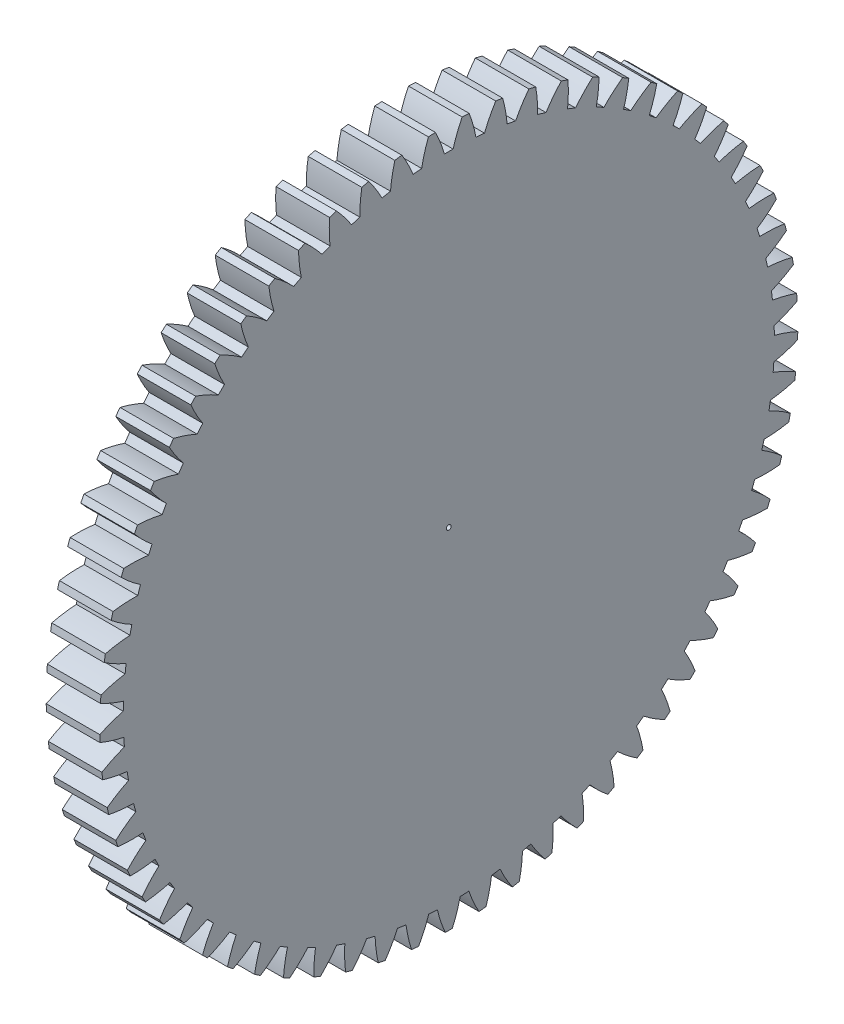
SolidWorks part; units mm, degrees
ref_plane "Plane1" through (0, 0, 0) normal (0, 0, 1) x (1, 0, 0)
ref_plane "Plane2" through (0, 0, 0) normal (0, 1, 0) x (1, 0, 0)
ref_plane "Plane3" through (0, 0, 0) normal (1, 0, 0) x (0, 0, -1)
other "Configuration Table"
sketch "HoldingSke" plane through (0, 0, 0) normal (0, 1, 0) x (1, 0, 0)
  line L0 (0, 0) -> (0.2415, -0.5179)
  line L1 (-15, 0) -> (100, 0) construction
  line L2 (0, 0) -> (-2.1039, 2.3779)
  line L3 (0, 0) -> (-11.863, 4.5341)
  line L4 (0, 0) -> (3.6497, 7.8269)
  line L5 (0, 0) -> (-46.8476, -17.4728)
  line L6 (0, 0) -> (-7.4607, -5.0337)
  line L7 (-2.1039, 2.3779) -> (8.6586, 51.2059)
  line L8 (-76.2, 54.61) -> (-76.1, 54.61)
  line L9 (-71.009, 38.7566) -> (-53.1078, 45.2721)
  line L10 (-76.2, 71.12) -> (104.1128, 71.12)
  line L11 (0, 0) -> (-9, 0)
  line L12 (-76.2, 101.6) -> (-76.147, 101.6)
  line L13 (24.9733, 27.94) -> (52.9518, 28.4284)
  line L14 (24.9733, 27.94) -> (24.9743, 27.94)
  line L15 (24.9733, 27.94) -> (100.4006, 29.5858)
  line L16 (-63.627, -1.75) -> (-12.827, -1.75)
  circle A0 centre (0, 0) radius 0.4
  circle A1 centre (0, 0) radius 37.5
  circle A2 centre (0, 0) radius 37.5
  circle A3 centre (0, 0) radius 0.4
  dimension "MHD" = 75
  dimension "Hub_dia" = 75
  dimension "Bore" = 0.8
  dimension "MBD" = 0.8
  dimension "Num_teeth" = 65
  dimension "Pitch" = 0.5714
  dimension "Overall_len" = 50
  dimension "Show_teeth" = 65
  dimension "Thickness" = 9
  dimension "OAL" = 50.0001
  dimension "T_dim" = 0.1
  dimension "Ap" = 20
  dimension "H" = 19.05
  dimension "Pitch_radius" = 180.3128
  dimension "Width" = 9
  dimension "Backlash" = 0.053
  dimension "Addendum_fac" = 1
  dimension "Dedendum_fac" = 1.25
  dimension "Clearance_fac" = 0.25
  dimension "Dedendum_add" = 0.001
  dimension "Module" = 1.75
sketch "BasProSke" plane through (0, 0, 0) normal (0, 1, 0) x (1, 0, 0)
  line L0 (-10, 0) -> (60, 0) construction
  line L1 (0, 0) -> (0, 58.625)
  line L2 (0, 0) -> (9, 0)
  line L3 (9, 0) -> (9, 58.625)
  line L4 (9, 58.625) -> (0, 58.625)
  dimension "Thickness" = 9
  dimension "Diameter" = 117.25
revolve "Base-Revolve" add sketch "BasProSke" angle 360 about L0
sketch "TooCutSke" plane through (0, 0, 0) normal (1, 0, 0) x (0, 0, -1)
  line L1 (0, 0) -> (0, 107) construction
  line L2 (0, 0) -> (-1.4671, 56.8561) construction
  line L3 (0, 0) -> (-5.4943, 113.5883) construction
  line L4 (-1.4671, 56.8561) -> (-2.7471, 56.7942) construction
  arc A0 (0.7251, 54.6817) -> (-0.7251, 54.6817) centre (0, 0) ccw
  arc A1 (2.2522, 58.6071) -> (-2.2522, 58.6071) centre (0, 0) ccw
  circle A2 centre (0, 0) radius 56.875 construction
  circle A3 centre (0, 0) radius 53.445 construction
  arc A4 (-0.7251, 54.6817) -> (-2.2522, 58.6071) centre (-22.5998, 48.4316) ccw
  arc A5 (2.2522, 58.6071) -> (0.7251, 54.6817) centre (22.5998, 48.4316) ccw
  dimension "Root_dia" = 109.373
  dimension "Overcut_dia" = 117.3008
  dimension "Pitch_dia" = 113.75
  dimension "Base_dia" = 106.89
  dimension "Flank_rad" = 22.75
  dimension "Half_ang" = 2.769
  dimension "Half_CT" = 1.2816
extrude "ToothCut" cut sketch "TooCutSke" along normal through all
fillet "Breaks" [suppressed] radius 0.035
fillet "RootFillets" [suppressed] radius 0.4385
pattern_circular "TeethCuts" count 65 every 5.538 about axis through (-10, 0, 0) along (1, 0, 0) of "ToothCut", "RootFillets", "Breaks"
sketch "HubNeaOneSke" plane through (0, 0, 0) normal (-1, 0, 0) x (0, 0, 1)
  circle A0 centre (0, 0) radius 37.5
  dimension "Diameter" = 75
extrude "HubNearOne" [suppressed] add sketch "HubNeaOneSke" along normal blind 41.0001
sketch "HubNeaBotSke" plane through (0, 0, 0) normal (-1, 0, 0) x (0, 0, 1)
  circle A0 centre (0, 0) radius 37.5
  dimension "Diameter" = 75
extrude "HubNearBoth" [suppressed] add sketch "HubNeaBotSke" along normal blind 20.5
ref_plane "FarPln" through (9, 0, 0) normal (1, 0, 0) x (0, 0, -1)
sketch "HubFarSke" plane through (9, 0, 0) normal (1, 0, 0) x (0, 0, -1)
  circle A0 centre (0, 0) radius 37.5
  dimension "Diameter" = 75
extrude "HubFar" [suppressed] add sketch "HubFarSke" along normal blind 20.5
sketch "BorSke" plane through (0, 0, 0) normal (1, 0, 0) x (0, 0, -1)
  circle A0 centre (0, 0) radius 0.4
  dimension "Diameter" = 0.8
extrude "Bore" cut sketch "BorSke" along normal mid plane 100.0001
sketch "KeySke" plane through (0, 0, 0) normal (1, 0, 0) x (0, 0, -1)
  line L0 (-0.05, 0) -> (-0.05, 0.5)
  line L1 (-0.05, 0.5) -> (0.05, 0.5)
  line L2 (0.05, 0.5) -> (0.05, 0)
  line L3 (0, 0) -> (0, 34) construction
  line L4 (-0.05, 0) -> (0.05, 0)
  dimension "Offset" = 0.5
  dimension "Width" = 0.1
extrude "Keyway" [suppressed] cut sketch "KeySke" along normal mid plane 100.0001
pattern_circular "Keyway2" [suppressed] count 2 every 90 about axis through (-10, 0, 0) along (1, 0, 0)
equation "' \"Module@HoldingSke\" = 6.35"
equation "' \"Num_teeth@HoldingSke\" = 12"
equation "' \"Ap@HoldingSke\" =  20"
equation "' \"Ap@HoldingSke\" = 20"
equation "' \"Width@HoldingSke\" = 0.5 * 25.4"
equation "' \"Hub_dia@HoldingSke\"= 1 * 25.4"
equation "' \"Hub_dia@HoldingSke\" = 1 * 25.4"
equation "' \"Overall_len@HoldingSke\" = 1.0 * 25.4"
equation "' \"Bore@HoldingSke\" = 0.75 * 25.4"
equation "' \"T_dim@HoldingSke\" = 0.1 * 25.4"
equation "' \"Width@KeySke\" = 0.25 * 25.4"
equation "' \"Show_teeth@HoldingSke\" = 13"
equation "' \"Backlash@HoldingSke\" = 0.009 * 25.4"
equation "' \"Addendum_fac@HoldingSke\" = 1.0"
equation "' \"Dedendum_fac@HoldingSke\" = 1.25"
equation "' \"Dedendum_add@HoldingSke\" = 0.00005 * 25.4"
equation "' \"Clearance_fac@HoldingSke\" = 0.25"
equation "\"Pitch@HoldingSke\" = 1 / \"Module@HoldingSke\""
equation "\"Overcut_dia@TooCutSke\" = (\"Num_teeth@HoldingSke\" + 2 * \"Addendum_fac@HoldingSke\") / \"Pitch@HoldingSke\" + 0.002 * 25.4"
equation "\"Pitch_dia@TooCutSke\" = \"Num_teeth@HoldingSke\" / \"Pitch@HoldingSke\""
equation "\"Base_dia@TooCutSke\" = \"Num_teeth@HoldingSke\" / \"Pitch@HoldingSke\" * cos((\"Ap@HoldingSke\"  * 3.14159265 / 180))"
equation "\"Root_dia@TooCutSke\" = (\"Num_teeth@HoldingSke\" + 2) / \"Pitch@HoldingSke\" - 2 * (\"Addendum_fac@HoldingSke\" + \"Dedendum_fac@HoldingSke\") / \"Pitch@HoldingSke\" - \"Dedendum_add@HoldingSke\" * 2"
equation "\"Half_ang@TooCutSke\" = 180 / \"Num_teeth@HoldingSke\""
equation "\"Half_CT@TooCutSke\" = \"Num_teeth@HoldingSke\" / \"Pitch@HoldingSke\" * sin((3.14159265 / 2 / \"Num_teeth@HoldingSke\")) / 2 - 7 * \"Backlash@HoldingSke\" / 4"
equation "\"Flank_rad@TooCutSke\" = \"Num_teeth@HoldingSke\" / \"Pitch@HoldingSke\" / 5"
equation "\"Radius@RootFillets\" = \"Clearance_fac@HoldingSke\" / \"Pitch@HoldingSke\" + \"Dedendum_add@HoldingSke\""
equation "\"Break_rad@Breaks\" = 0.02 / \"Pitch@HoldingSke\""
equation "\"Thickness@HoldingSke\" = \"Width@HoldingSke\""
equation "\"OAL@HoldingSke\" = \"Thickness@HoldingSke\""
equation "\"MHD@HoldingSke\" = (\"Num_teeth@HoldingSke\" + 2) / \"Pitch@HoldingSke\" - 2 * (\"Addendum_fac@HoldingSke\" + \"Dedendum_fac@HoldingSke\")  / \"Pitch@HoldingSke\" - \"Dedendum_add@HoldingSke\" * 2"
equation "\"MBD@HoldingSke\" = (\"Num_teeth@HoldingSke\" + 2) / \"Pitch@HoldingSke\" - 2 * (\"Addendum_fac@HoldingSke\" + \"Dedendum_fac@HoldingSke\")  / \"Pitch@HoldingSke\" - \"Dedendum_add@HoldingSke\" * 2 - 0.002 * 25.4"
equation "\"MHD@HoldingSke\" = ((sgn( \"MHD@HoldingSke\" - \"Hub_dia@HoldingSke\" )-1)*( \"MHD@HoldingSke\" - \"Hub_dia@HoldingSke\" ))/-2+ \"Hub_dia@HoldingSke\""
equation "\"MBD@HoldingSke\" = ((sgn( \"MBD@HoldingSke\" - \"Bore@HoldingSke\" )-1)*( \"MBD@HoldingSke\" - \"Bore@HoldingSke\" ))/-2+ \"Bore@HoldingSke\""
equation "\"OAL@HoldingSke\" = ((sgn( \"OAL@HoldingSke\" - \"Overall_len@HoldingSke\" )+1)*( \"OAL@HoldingSke\" - \"Overall_len@HoldingSke\" ))/2 + \"Overall_len@HoldingSke\" + 0.000002 * 25.4"
equation "\"Num_teeth@TeethCuts\" = int( \"Show_teeth@HoldingSke\" ) + 1"
equation "\"Num_teeth@TeethCuts\" = ((sgn( \"Num_teeth@TeethCuts\" - \"Num_teeth@HoldingSke\" )-1)*( \"Num_teeth@TeethCuts\" - \"Num_teeth@HoldingSke\" ))/-2+ \"Num_teeth@HoldingSke\""
equation "\"Num_teeth@TeethCuts\" = ((sgn( \"Num_teeth@TeethCuts\" - 2.0)+1)*( \"Num_teeth@TeethCuts\" - 2.0))/2 +2.0"
equation "\"Angle@TeethCuts\" = 360.0 / \"Num_teeth@HoldingSke\""
equation "\"Diameter@BasProSke\" = (\"Num_teeth@HoldingSke\" + 2 * \"Addendum_fac@HoldingSke\") / \"Pitch@HoldingSke\""
equation "\"Thickness@BasProSke\"  = \"Thickness@HoldingSke\""
equation "' \"Fillet_rad@BasProSke\" =  \"Thickness@HoldingSke\" * 0.05"
equation "' \"Fillet_rad@BasProSke\" = \"Thickness@HoldingSke\" * 0.05"
equation "\"MHD@HoldingSke\" = ((sgn( \"MHD@HoldingSke\" - \"Root_dia@TooCutSke\" )-1)*( \"MHD@HoldingSke\" - \"Root_dia@TooCutSke\" ))/-2+ \"Root_dia@TooCutSke\""
equation "\"Diameter@HubNeaOneSke\" = \"MHD@HoldingSke\""
equation "\"Length@HubNearOne\" = \"OAL@HoldingSke\" - \"Thickness@BasProSke\""
equation "\"Diameter@HubNeaBotSke\" = \"MHD@HoldingSke\""
equation "\"Length@HubNearBoth\" = ( \"OAL@HoldingSke\" - \"Thickness@BasProSke\" ) / 2.0"
equation "\"Thickness@FarPln\" = \"Thickness@BasProSke\""
equation "\"Diameter@HubFarSke\" = \"MHD@HoldingSke\""
equation "\"Length@HubFar\" = ( \"OAL@HoldingSke\" - \"Thickness@BasProSke\" ) / 2.0"
equation "\"Diameter@BorSke\" = \"MBD@HoldingSke\""
equation "\"D1@Bore\" = \"OAL@HoldingSke\" * 2.0"
equation "\"D1@Keyway\" = \"OAL@HoldingSke\" * 2.0"
equation "\"Offset@KeySke\" = \"T_dim@HoldingSke\" + \"MBD@HoldingSke\" / 2.0"
